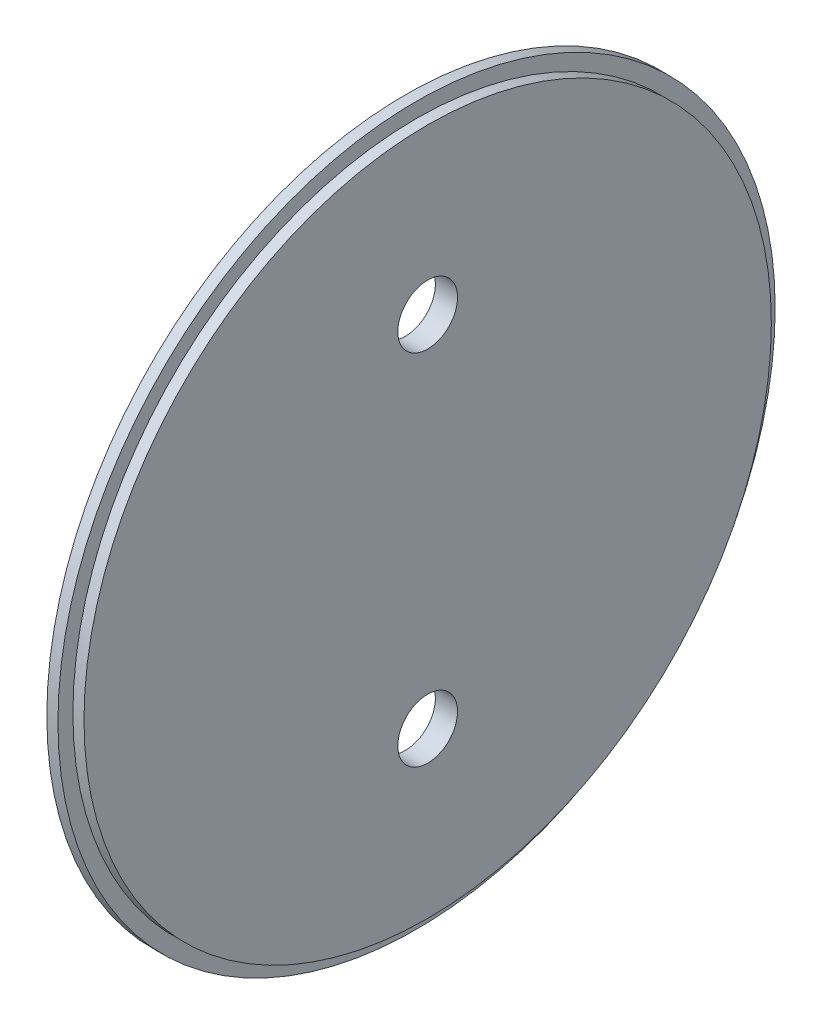
SolidWorks part; units mm, degrees
ref_plane "Front Plane" through (0, 0, 0) normal (1, 0, 0) x (0, 1, 0)
ref_plane "Top Plane" through (0, 0, 0) normal (0, 0, 1) x (0, 1, 0)
ref_plane "Right Plane" through (0, 0, 0) normal (0, 1, 0) x (-1, 0, 0)
sketch "Sketch1" plane through (0, 0, 0) normal (1, 0, 0) x (0, 1, 0)
  circle A0 centre (0, 0) radius 38.1
  dimension "D1" = 76.2
extrude "Boss-Extrude1" add sketch "Sketch1" along normal blind 1.1811
sketch "Sketch2" plane through (1.1811, 0, 0) normal (1, 0, 0) x (0, 1, 0)
  circle A0 centre (0, 0) radius 36.5125
  dimension "D1" = 73.025
extrude "Boss-Extrude2" add sketch "Sketch2" along normal blind 1.1811
sketch "Sketch3" plane through (0, 0, 0) normal (-1, 0, 0) x (0, -1, 0)
  circle A1 centre (19.05, 0) radius 3.175
  circle A2 centre (-19.05, 0) radius 3.175
  point P0 (0, 0)
  dimension "D1" = 19.05
  dimension "D2" = 6.35
  dimension "D3" = 6.35
  dimension "D4" = 19.05
extrude "Cut-Extrude1" cut sketch "Sketch3" against normal through all
